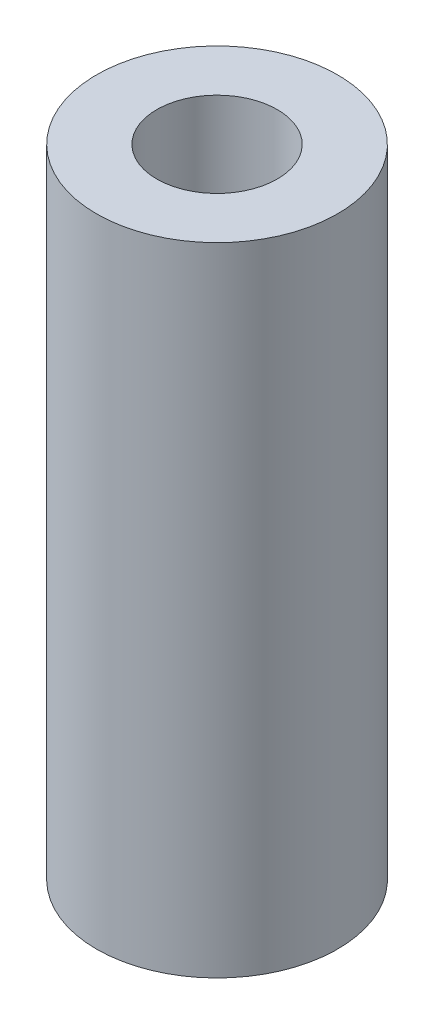
SolidWorks part; units mm, degrees
ref_plane "前视基准面" through (0, 0, 0) normal (0, 0, 1) x (1, 0, 0)
ref_plane "上视基准面" through (0, 0, 0) normal (0, 1, 0) x (1, 0, 0)
ref_plane "右视基准面" through (0, 0, 0) normal (1, 0, 0) x (0, 0, -1)
other "Configuration Table"
sketch "草图1" plane through (0, 0, 0) normal (0, 1, 0) x (1, 0, 0)
  circle A0 centre (0, 0) radius 1.75
  circle A1 centre (0, 0) radius 3.5
  dimension "D1" = 3.5
  dimension "D2" = 7
extrude "凸台-拉伸1" add sketch "草图1" along normal blind 18.5
